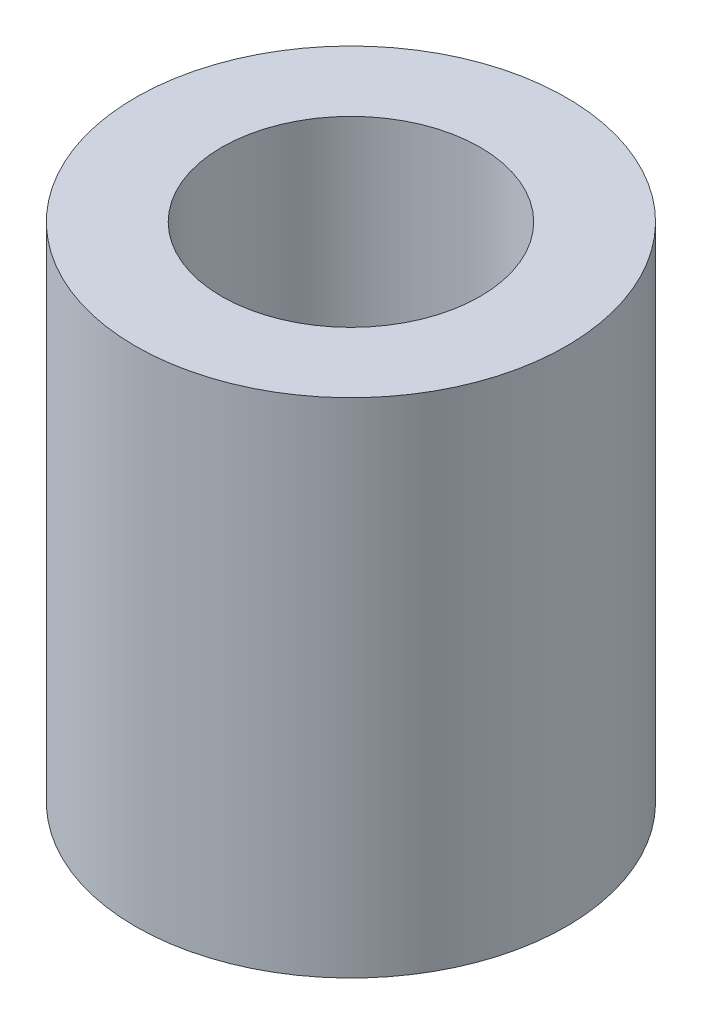
SolidWorks part; units mm, degrees
material "ABS"
ref_plane "前视基准面" through (0, 0, 0) normal (0, 0, 1) x (1, 0, 0)
ref_plane "上视基准面" through (0, 0, 0) normal (0, 1, 0) x (1, 0, 0)
ref_plane "右视基准面" through (0, 0, 0) normal (1, 0, 0) x (0, 0, -1)
other "Configuration Table"
sketch "草图1" plane through (0, 0, 0) normal (0, 1, 0) x (1, 0, 0)
  circle A0 centre (0, 0) radius 1.8
  circle A1 centre (0, 0) radius 3
  dimension "D1" = 3.6
  dimension "D2" = 6
extrude "凸台-拉伸1" add sketch "草图1" along normal blind 7
